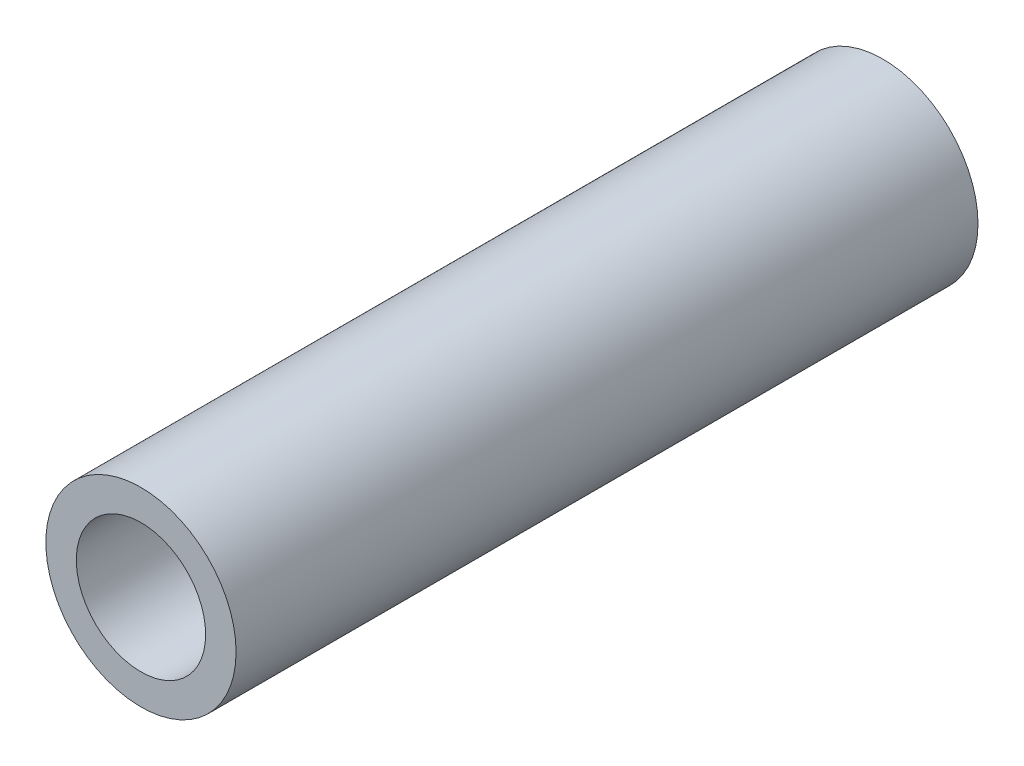
SolidWorks part; units mm, degrees
ref_plane "前视基准面" through (0, 0, 0) normal (0, 0, 1) x (1, 0, 0)
ref_plane "上视基准面" through (0, 0, 0) normal (0, 1, 0) x (1, 0, 0)
ref_plane "右视基准面" through (0, 0, 0) normal (1, 0, 0) x (0, 0, -1)
sketch "草图1" plane through (0, 0, 0) normal (0, 0, 1) x (1, 0, 0)
  circle A0 centre (0, 0) radius 5.1
  circle A1 centre (0, 0) radius 7.5
  dimension "D1" = 10.2
  dimension "D2" = 15
extrude "凸台-拉伸1" add sketch "草图1" along normal blind 58.5
